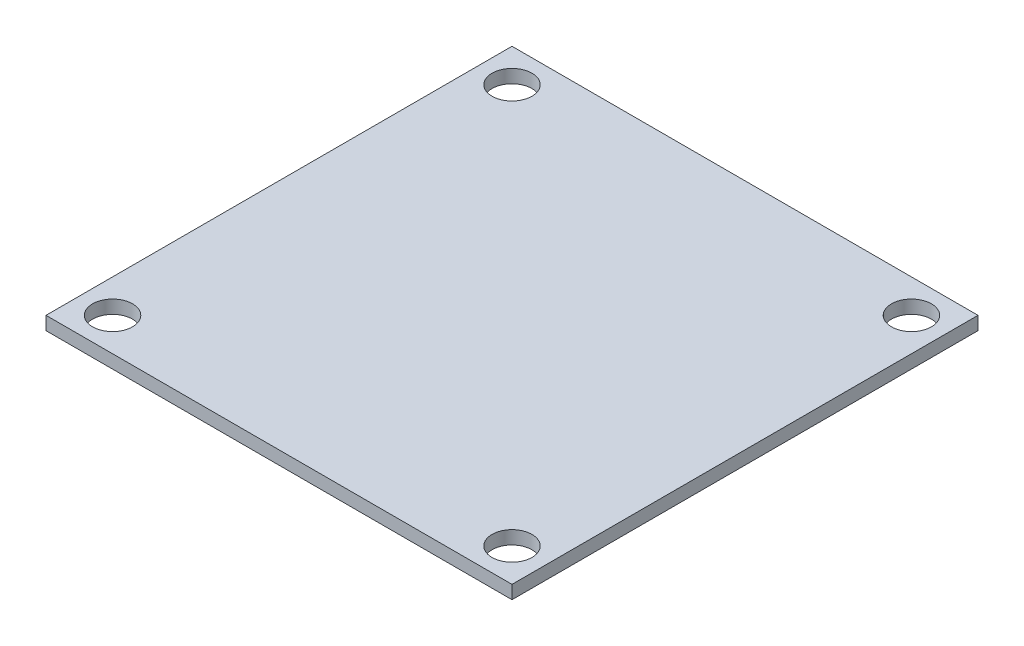
SolidWorks part; units mm, degrees
ref_plane "前视基准面" through (0, 0, 0) normal (0, 0, 1) x (1, 0, 0)
ref_plane "上视基准面" through (0, 0, 0) normal (0, 1, 0) x (1, 0, 0)
ref_plane "右视基准面" through (0, 0, 0) normal (1, 0, 0) x (0, 0, -1)
sketch "草图1" plane through (0, 0, 0) normal (0, 1, 0) x (1, 0, 0)
  line L1 (-35, 35) -> (35, 35)
  line L2 (-35, 35) -> (-35, -35)
  line L3 (-35, -35) -> (35, -35)
  line L4 (35, 35) -> (35, -35)
  line L5 (-35, 35) -> (35, -35) construction
  line L6 (-35, -35) -> (35, 35) construction
  point P0 (0, 0)
  point P6 (0, 0)
extrude "凸台-拉伸2" add sketch "草图1" along normal blind 2
sketch "草图3" plane through (0, 2, 0) normal (0, 1, 0) x (1, 0, 0)
  circle A0 centre (-30, 30) radius 3
  circle A2 centre (30, 30) radius 3
  circle A3 centre (-30, -30) radius 3
  circle A4 centre (30, -30) radius 3
  dimension "D1" = 2
  dimension "D2" = 2
  dimension "D3" = 2
extrude "切除-拉伸1" cut sketch "草图3" against normal through all
